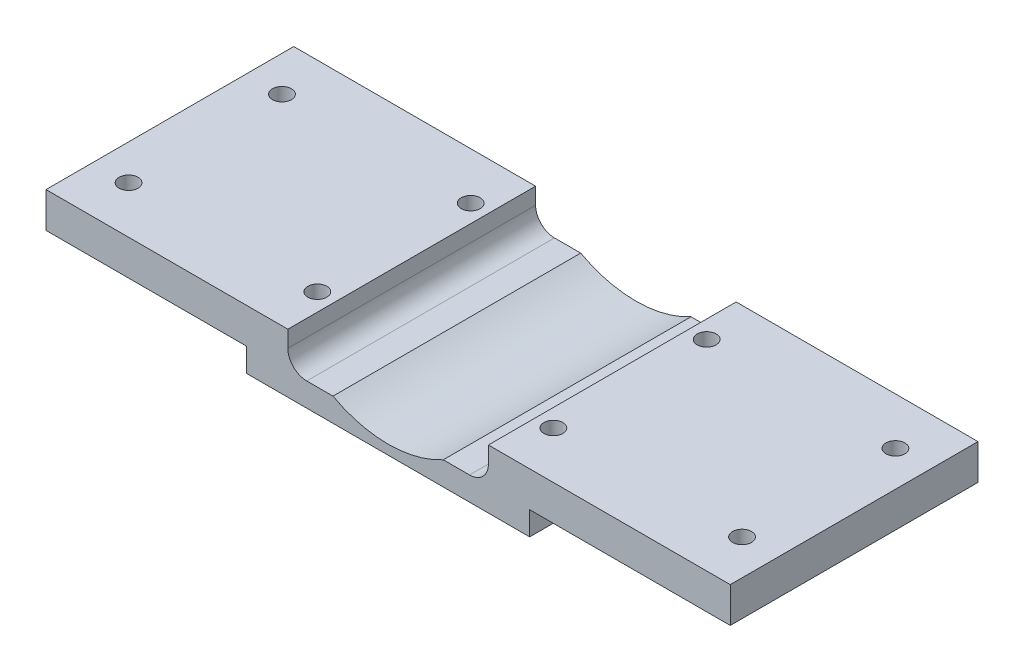
SolidWorks part; units mm, degrees
ref_plane "Front Plane" through (0, 0, 0) normal (0, 0, 1) x (1, 0, 0)
ref_plane "Top Plane" through (0, 0, 0) normal (0, 1, 0) x (1, 0, 0)
ref_plane "Right Plane" through (0, 0, 0) normal (1, 0, 0) x (0, 0, -1)
sketch "Sketch1" plane through (0, 0, 0) normal (0, 1, 0) x (1, 0, 0)
  line L1 (0, 0) -> (184.15, 0)
  line L2 (0, 0) -> (0, 66.675)
  line L3 (0, 66.675) -> (184.15, 66.675)
  line L4 (184.15, 0) -> (184.15, 66.675)
  dimension "D1" = 184.15
  dimension "D2" = 66.675
extrude "Boss-Extrude1" add sketch "Sketch1" along normal blind 9.525
sketch "Sketch4" plane through (0, 0, 0) normal (0, 0, 1) x (1, 0, 0)
  line L0 (0, 0) -> (184.15, 0) construction
  line L1 (53.975, 0) -> (130.175, 0)
  line L2 (53.975, 0) -> (53.975, -6.35)
  line L3 (53.975, -6.35) -> (130.175, -6.35)
  line L4 (130.175, 0) -> (130.175, -6.35)
  line L5 (92.075, 9.525) -> (92.075, -52.0257) construction
  line L6 (0, 9.525) -> (184.15, 9.525) construction
  dimension "D1" = 76.2
  dimension "D2" = 6.35
extrude "Boss-Extrude2" add sketch "Sketch4" against normal up to surface (66.675 mm away) up to face at (92.075, 4.7625, -66.675)
sketch "Sketch5" plane through (0, 9.525, 0) normal (0, 1, 0) x (1, 0, 0)
  line L0 (184.15, 66.675) -> (0, 66.675) construction
  line L1 (119.0625, 66.675) -> (65.0875, 66.675)
  line L2 (119.0625, 66.675) -> (119.0625, 0)
  line L3 (119.0625, 0) -> (65.0875, 0)
  line L4 (65.0875, 66.675) -> (65.0875, 0)
  line L5 (0, 0) -> (184.15, 0) construction
  line L6 (92.075, 66.675) -> (92.075, -25.2417) construction
  dimension "D1" = 53.975
extrude "Cut-Extrude1" cut sketch "Sketch5" against normal blind 9.525
hole_wizard "#10 Clearance Hole1" positions "Sketch2" profile "Sketch3" hole size "#10" standard "ANSI Inch"
sketch "Sketch2" plane through (0, 9.525, 0) normal (0, 1, 0) x (1, 0, 0)
  line L0 (0, 66.675) -> (0, 0) construction
  line L1 (184.15, 66.675) -> (119.0625, 66.675) construction
  line L2 (0, 0) -> (65.0875, 0) construction
  line L3 (184.15, 0) -> (184.15, 66.675) construction
  line L4 (184.15, 66.675) -> (130.175, 66.675) construction
  line L7 (130.175, 66.675) -> (53.975, 66.675) construction
  point P0 (9.525, 53.975)
  point P2 (9.525, 12.7)
  point P4 (60.325, 12.7)
  point P6 (60.325, 53.975)
  point P8 (123.825, 53.975)
  point P10 (123.8498, 12.7)
  point P12 (174.625, 12.7)
  point P14 (174.625, 53.975)
  dimension "D1" = 9.525
  dimension "D2" = 12.7
  dimension "D3" = 9.525
  dimension "D4" = 12.7
  dimension "D5" = 12.7
  dimension "D6" = 50.8
  dimension "D7" = 12.7
  dimension "D8" = 50.8
  dimension "D9" = 41.275
  dimension "D10" = 9.525
  dimension "D11" = 12.7
  dimension "D12" = 9.525
  dimension "D13" = 50.8
  dimension "D14" = 41.275
  dimension "D15" = 12.7
sketch "Sketch3" plane through (9.525, 9.525, -53.975) normal (1, 0, 0) x (0, 0, 1)
  line L0 (0, 0) -> (0, 9.525)
  line L1 (0, 9.525) -> (2.5527, 9.525)
  line L2 (2.5527, 9.525) -> (2.5527, 0)
  line L5 (2.5527, 0) -> (0, 0)
  line L11 (0, -6.35) -> (0, 107.95) construction
  dimension "Thru Hole Dia." = 5.1054
  dimension "Thru Hole Depth" = 9.525
ref_plane "Plane1" through (92.075, 0, 0) normal (-1, 0, 0) x (0, 0, 1)
sketch "Sketch12" plane through (0, 0, -66.675) normal (0, 0, -1) x (-1, 0, 0)
  circle A0 centre (-92.075, 27.2394) radius 31.0193
extrude "Cut-Extrude3" cut sketch "Sketch12" against normal through all contours A0
fillet "Fillet8" radius 5.08 1 edges at (65.0875, 0, -33.3375)
fillet "Fillet9" radius 5.08 1 edges at (119.0625, 0, -33.3375)
sketch "Sketch13" plane through (0, 0, 0) normal (0, 0, 1) x (1, 0, 0)
  line L0 (53.975, -6.35) -> (130.175, -6.35) construction
  line L1 (53.975, 0) -> (130.175, 0)
  line L2 (53.975, 0) -> (53.975, -6.35)
  line L3 (53.975, -6.35) -> (130.175, -6.35)
  line L4 (130.175, 0) -> (130.175, -6.35)
extrude "Cut-Extrude4" [suppressed] cut sketch "Sketch13" against normal through all
sketch "Sketch14" [suppressed] plane through (0, 0, 0) normal (0, 0, 1) x (1, 0, 0)
  line L2 (113.9825, 0) -> (184.15, 0) construction
  line L3 (119.0625, 5.08) -> (119.0625, 9.525) construction
  line L5 (113.9825, 0) -> (119.0625, 0)
  line L6 (119.0625, 5.08) -> (119.0625, 0)
  arc A0 (113.9825, 0) -> (119.0625, 5.08) centre (113.9825, 5.08) ccw construction
  arc A2 (113.9825, 0) -> (119.0625, 5.08) centre (113.9825, 5.08) ccw
extrude "Cut-Extrude5" [suppressed] cut sketch "Sketch14" against normal through all
sketch "Sketch15" [suppressed] plane through (0, 0, 0) normal (0, 0, 1) x (1, 0, 0)
  line L0 (0, 0) -> (70.1675, 0) construction
  line L1 (65.0875, 5.08) -> (65.0875, 9.525) construction
  line L2 (65.0875, 0) -> (70.1675, 0)
  line L3 (65.0875, 5.08) -> (65.0875, 0)
  arc A0 (65.0875, 5.08) -> (70.1675, 0) centre (70.1675, 5.08) ccw construction
  arc A1 (65.0875, 5.08) -> (70.1675, 0) centre (70.1675, 5.08) ccw
extrude "Cut-Extrude6" [suppressed] cut sketch "Sketch15" against normal through all
sketch "Sketch16" [suppressed] plane through (0, 0, 0) normal (0, 0, 1) x (1, 0, 0)
  line L1 (0, 9.525) -> (184.15, 9.525)
  line L2 (0, 9.525) -> (0, 0)
  line L3 (0, 0) -> (184.15, 0)
  line L4 (184.15, 9.525) -> (184.15, 0)
extrude "Cut-Extrude7" [suppressed] cut sketch "Sketch16" against normal through all
